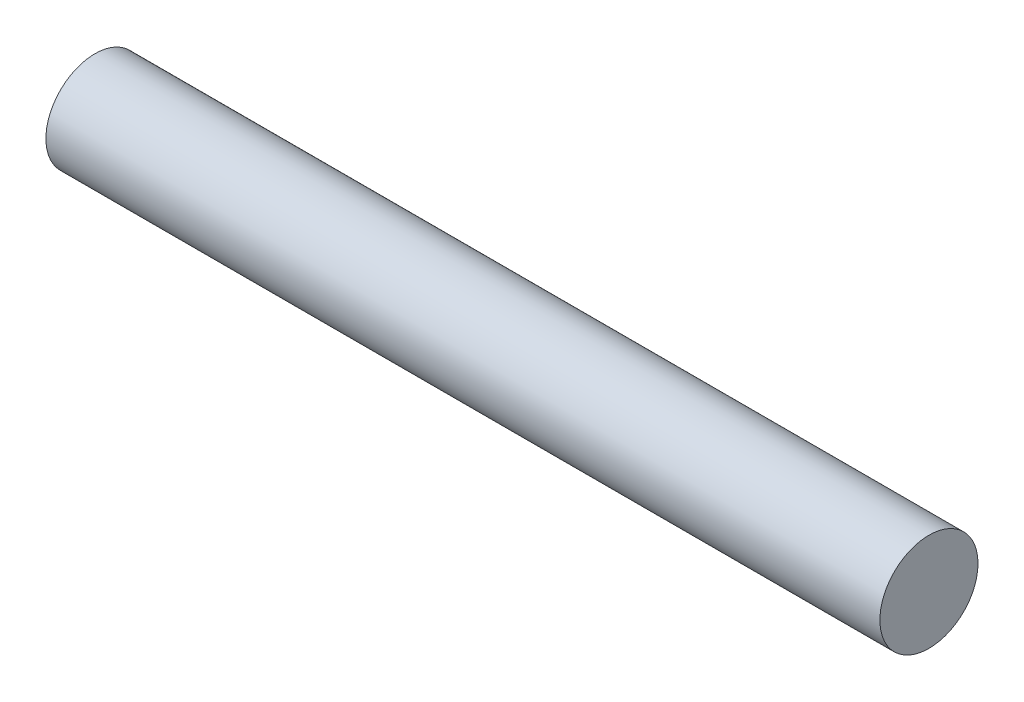
SolidWorks part; units mm, degrees
material "6061 Alloy"
ref_plane "Front Plane" through (0, 0, 0) normal (0, 0, 1) x (1, 0, 0)
ref_plane "Top Plane" through (0, 0, 0) normal (0, 1, 0) x (1, 0, 0)
ref_plane "Right Plane" through (0, 0, 0) normal (1, 0, 0) x (0, 0, -1)
sketch "Sketch1" plane through (0, 0, 0) normal (1, 0, 0) x (0, 0, -1)
  circle A0 centre (0, 0) radius 4
  dimension "D1" = 8
extrude "Boss-Extrude1" add sketch "Sketch1" along normal blind 68
